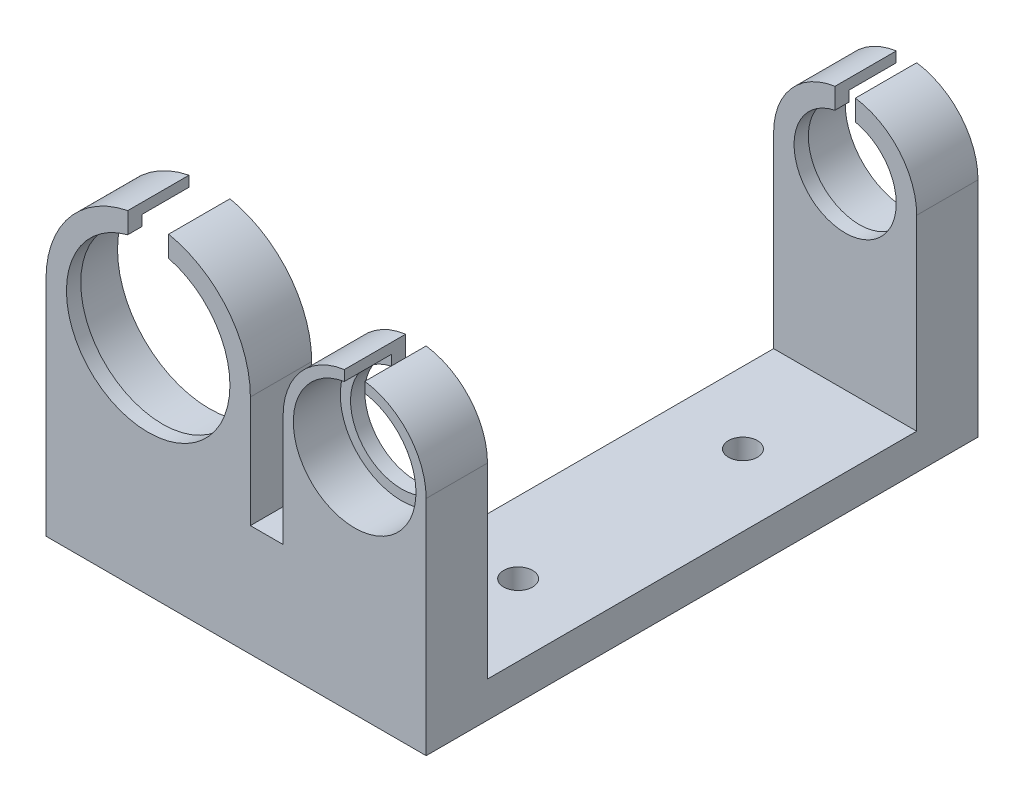
SolidWorks part; units mm, degrees
ref_plane "Front Plane" through (0, 0, 0) normal (0, 0, 1) x (1, 0, 0)
ref_plane "Top Plane" through (0, 0, 0) normal (0, 1, 0) x (1, 0, 0)
ref_plane "Right Plane" through (0, 0, 0) normal (1, 0, 0) x (0, 0, -1)
sketch "Sketch1" plane through (0, 0, 0) normal (0, 0, 1) x (1, 0, 0)
  line L0 (8.89, 0) -> (8.89, -27.686)
  line L1 (-8.89, 0) -> (-8.89, -27.686)
  line L2 (-8.89, -27.686) -> (8.89, -27.686)
  line L3 (-8.89, 0) -> (-1.27, 0)
  line L4 (8.89, 0) -> (1.27, 0)
  line L5 (-1.27, 0) -> (-1.27, 8.7988)
  line L6 (1.27, 0) -> (1.27, 8.7988)
  line L7 (-12.954, 0) -> (-12.954, -27.686)
  line L8 (-12.954, -27.686) -> (-38.354, -27.686)
  line L9 (-38.354, -27.686) -> (-38.354, 0)
  line L10 (-38.354, 0) -> (-28.194, 0)
  line L11 (-12.954, 0) -> (-23.114, 0)
  line L12 (-28.194, 0) -> (-28.194, 12.4434)
  line L13 (-23.114, 0) -> (-23.114, 12.4434)
  line L14 (-12.954, -27.686) -> (-8.89, -27.686)
  line L15 (-12.954, -13.843) -> (-8.89, -13.843)
  circle A0 centre (0, 0) radius 7.62
  circle A1 centre (0, 0) radius 8.89
  circle A2 centre (-25.654, 0) radius 11.43
  circle A3 centre (-25.654, 0) radius 12.7
  dimension "D1" = 15.24
  dimension "D2" = 17.78
  dimension "D7" = 22.86
  dimension "D8" = 25.4
  dimension "D3" = 27.686
  dimension "D4" = 27.686
  dimension "D5" = 7.62
  dimension "D6" = 7.62
  dimension "D9" = 4.064
  dimension "D10" = 10.16
  dimension "D11" = 10.16
extrude "Boss-Extrude1" add sketch "Sketch1" against normal blind 7.62 contours A3 L9 L8 L7 | A1 L1 L2 L0 | L3 A1 L4 A0 | L5 A1 L3 A0 | L4 A1 L6 A0 | L10 A3 L11 A2 | L11 A3 L13 A2 | L12 A3 L10 A2 | L15 L7 L14 L1
sketch "Sketch2" plane through (0, 0, -7.62) normal (0, 0, -1) x (-1, 0, 0)
  line L0 (-1.27, 7.5134) -> (-1.27, 6.2217)
  line L1 (1.27, 7.5134) -> (1.27, 6.2217)
  circle A0 centre (0, 0) radius 6.35
  circle A1 centre (0, 0) radius 7.62
  arc M14 (1.27, 7.5134) -> (-1.27, 7.5134) centre (0, 0) cw
  dimension "D1" = 12.7
  dimension "D2" = 15.24
extrude "Boss-Extrude2" add sketch "Sketch2" against normal blind 1.778 contours A0 L0 L1 M14
sketch "Sketch3" plane through (0, 0, 0) normal (0, 0, 1) x (1, 0, 0)
  line L0 (-28.194, 11.1442) -> (-28.194, 9.8374)
  line L1 (-23.114, 11.1442) -> (-23.114, 9.8374)
  circle A0 centre (-25.654, 0) radius 10.16
  circle A1 centre (-25.654, 0) radius 11.43
  arc M12 (-23.114, 11.1442) -> (-28.194, 11.1442) centre (-25.654, 0) cw
  dimension "D1" = 22.86
  dimension "D2" = 20.32
extrude "Boss-Extrude3" add sketch "Sketch3" against normal blind 1.778 contours A0 L0 L1 M12
sketch "Sketch4" plane through (0, 0, -7.62) normal (0, 0, -1) x (-1, 0, 0)
  line L1 (-8.89, -27.686) -> (8.89, -27.686)
  line L2 (-8.89, -27.686) -> (-8.89, -23.241)
  line L3 (-8.89, -23.241) -> (8.89, -23.241)
  line L4 (8.89, -27.686) -> (8.89, -23.241)
  dimension "D1" = 17.78
  dimension "D2" = 4.445
extrude "Boss-Extrude4" add sketch "Sketch4" along normal blind 60.96
ref_plane "Plane1" through (0, 0, -34.29) normal (0, 0, -1) x (-1, 0, 0)
sketch "Sketch5" plane through (0, 0, -68.58) normal (0, 0, -1) x (-1, 0, 0)
  line L0 (8.89, 0) -> (8.89, -27.686)
  line L1 (-8.89, 0) -> (-8.89, -27.686)
  line L2 (-8.89, -27.686) -> (8.89, -27.686)
  line L3 (-1.27, 8.7988) -> (-1.27, 7.5134)
  line L4 (1.27, 8.7988) -> (1.27, 7.5103)
  line L5 (1.27, 6.2217) -> (1.27, 8.7988) construction
  circle A0 centre (0, 0) radius 8.89
  circle A1 centre (0, 0) radius 7.62
  line M4 (8.89, -23.241) -> (-8.89, -23.241)
  dimension "D1" = 15.24
extrude "Boss-Extrude5" add sketch "Sketch5" against normal blind 7.62 contours A0 L1 L0 M4 | A1 L3 A0 L4
mirror "Mirror1" about plane through (0, 0, -34.29) normal (0, 0, -1) of "Boss-Extrude2"
sketch "Sketch6" plane through (0, -23.241, 0) normal (0, 1, 0) x (1, 0, 0)
  line L0 (6.35, 7.62) -> (-6.35, 7.62) construction
  line L1 (-8.89, 60.96) -> (8.89, 60.96) construction
  line L2 (8.89, 60.96) -> (8.89, 7.62) construction
  circle A0 centre (0, 20.32) radius 2.54
  circle A1 centre (0, 48.26) radius 2.54
  dimension "D1" = 5.08
  dimension "D2" = 5.08
  dimension "D3" = 12.7
  dimension "D4" = 12.7
  dimension "D5" = 8.89
hole_wizard "M3 Clearance Hole1" positions "Sketch7" profile "Sketch8" hole size "M3" standard "ANSI Metric"
sketch "Sketch7" plane through (0, -23.241, 0) normal (0, 1, 0) x (1, 0, 0)
  point P0 (0, 20.32)
  point P3 (0, 48.26)
sketch "Sketch8" plane through (0, -23.241, -20.32) normal (1, 0, 0) x (0, 0, 1)
  line L0 (0, 0) -> (0, 26.4815)
  line L1 (0, 26.4815) -> (1.8, 25.4)
  line L2 (1.8, 25.4) -> (1.8, 0)
  line L5 (1.8, 0) -> (0, 0)
  line L10 (0, 26.4815) -> (-1.8, 25.4) construction
  line L11 (0, -6.35) -> (0, 107.95) construction
  dimension "Hole Dia." = 3.6
  dimension "Hole Depth" = 25.4
  dimension "Drill Angle" = 118
